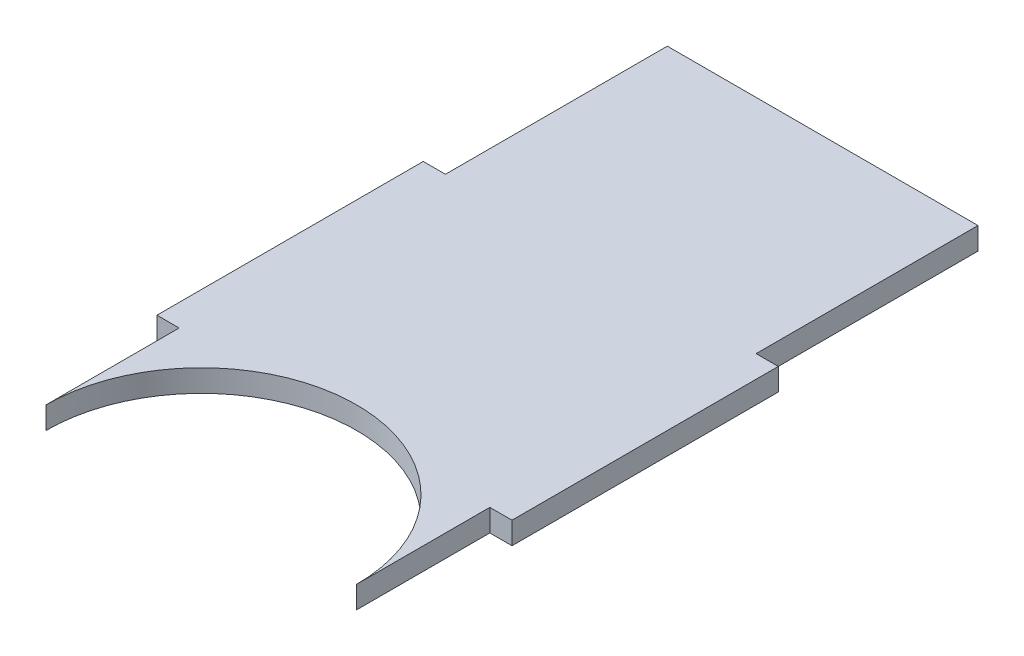
SolidWorks part; units mm, degrees
material "AISI 4130 Steel, annealed at 865C"
ref_plane "X-Y Datum" through (0, 0, 0) normal (0, 0, 1) x (1, 0, 0)
ref_plane "X-Z Datum" through (0, 0, 0) normal (0, 1, 0) x (1, 0, 0)
ref_plane "Y-Z Datum" through (0, 0, 0) normal (1, 0, 0) x (0, 0, -1)
sketch "Sketch1" plane through (0, 0, 0) normal (0, 1, 0) x (1, 0, 0)
  line L0 (12.7, 0) -> (0, 0) construction
  line L1 (11.1125, 25.4) -> (-11.1125, 25.4)
  line L2 (11.1125, 25.4) -> (11.1125, -19.05)
  line L3 (11.1125, -19.05) -> (-11.1125, -19.05) construction
  line L4 (-11.1125, 25.4) -> (-11.1125, -19.05)
  line L5 (0, 0) -> (0, 25.4) construction
  line L7 (11.1125, -9.525) -> (12.7, -9.525)
  line L8 (11.1125, -9.525) -> (11.1125, 9.525)
  line L9 (11.1125, 9.525) -> (12.7, 9.525)
  line L10 (12.7, -9.525) -> (12.7, 9.525)
  line L11 (-11.1125, -9.525) -> (-12.7, -9.525)
  line L12 (-11.1125, -9.525) -> (-11.1125, 9.525)
  line L13 (-11.1125, 9.525) -> (-12.7, 9.525)
  line L14 (-12.7, -9.525) -> (-12.7, 9.525)
  arc A2 (11.1125, -19.05) -> (-11.1125, -19.05) centre (0, -19.05) ccw
  dimension "D5" = 44.45
  dimension "D4" = 25.4
  dimension "D1" = 1.5875
  dimension "D2" = 25.4
  dimension "D3" = 19.05
extrude "Boss-Extrude1" add sketch "Sketch1" along normal blind 1.5875
